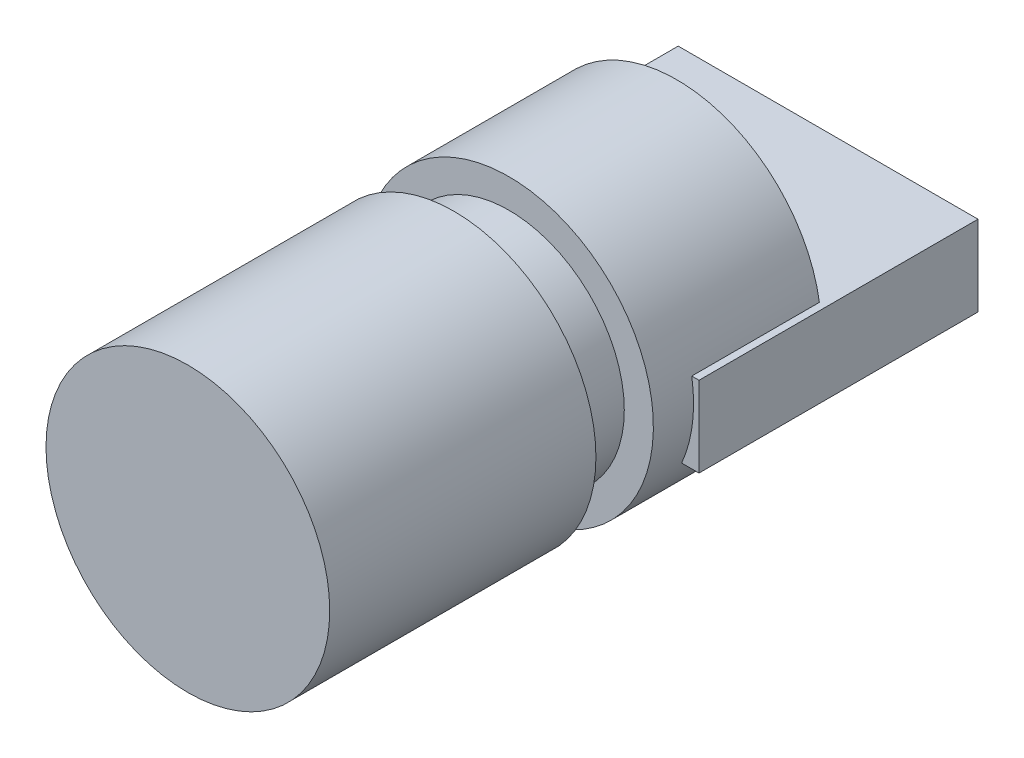
SolidWorks part; units mm, degrees
ref_plane "Front Plane" through (0, 0, 0) normal (0, 0, 1) x (1, 0, 0)
ref_plane "Top Plane" through (0, 0, 0) normal (0, 1, 0) x (1, 0, 0)
ref_plane "Right Plane" through (0, 0, 0) normal (1, 0, 0) x (0, 0, -1)
sketch "Sketch3" plane through (0, 0, 0) normal (0, 0, 1) x (1, 0, 0)
  circle A0 centre (-7.6717, 4.7989) radius 3
  dimension "D1" = 6
extrude "Boss-Extrude1" add sketch "Sketch3" along normal blind 5.63
sketch "Sketch8" plane through (0, 0, 0) normal (0, 0, -1) x (-1, 0, 0)
  circle A0 centre (7.6717, 4.7989) radius 2.44
  circle A1 centre (7.6717, 4.7989) radius 3 construction
  point P2 (0, 0)
  dimension "D1" = 4.88
extrude "Boss-Extrude2" add sketch "Sketch8" along normal blind 1.16
sketch "Sketch9" plane through (0, 0, -1.16) normal (0, 0, -1) x (-1, 0, 0)
  circle A0 centre (7.6717, 4.7989) radius 3.055
  circle A1 centre (7.6717, 4.7989) radius 2.44 construction
  dimension "D1" = 6.11
extrude "Boss-Extrude3" add sketch "Sketch9" along normal blind 3.55
sketch "Sketch12" plane through (0, 0, 5.63) normal (0, 0, 1) x (1, 0, 0)
  line L0 (-10.6717, 4.7989) -> (-4.6717, 4.7989) construction
  line L1 (-7.6717, 7.7989) -> (-7.6717, 1.7989) construction
  circle A0 centre (-7.6717, 4.7989) radius 3 construction
sketch "Sketch13" plane through (0, 0, -4.71) normal (0, 0, -1) x (-1, 0, 0)
  line L0 (4.6167, 4.7989) -> (10.7267, 4.7989) construction
  line L1 (7.6717, 7.8539) -> (7.6717, 1.7439) construction
  circle A0 centre (7.6717, 4.7989) radius 3.055 construction
ref_plane "Horizontal Plane" through (0, 4.7989, 0) normal (0, 1, 0) x (1, 0, 0)
ref_plane "Face Plane" through (0, 0, 5.63) normal (0, 0, 1) x (1, 0, 0)
ref_plane "Vertical Plane" through (-7.6717, 0, 0) normal (-1, 0, 0) x (0, 0, 1)
sketch "Sketch15" plane through (0, 4.7989, 0) normal (0, 1, 0) x (1, 0, 0)
  line L1 (-10.7267, 1.16) -> (-4.6167, 1.16) construction
  line L2 (-10.8417, 2.01) -> (-4.5017, 2.01)
  line L3 (-10.8417, 2.01) -> (-10.8417, 7.91)
  line L4 (-10.8417, 7.91) -> (-4.5017, 7.91)
  line L6 (-4.5017, 2.01) -> (-4.5017, 7.91)
  line L7 (-10.8417, 2.01) -> (-4.5017, 7.91) construction
  line L8 (-10.8417, 7.91) -> (-4.5017, 2.01) construction
  line L9 (-4.6167, 4.71) -> (-10.7267, 4.71) construction
  point P0 (-7.6717, 4.96)
  point P7 (0, 0)
  point P10 (0, 0)
  point P11 (0, 0)
  point P12 (-7.6717, 4.71)
  dimension "D1" = 5.9
  dimension "D2" = 6.34
  dimension "D3" = 6.75
extrude "Boss-Extrude4" add sketch "Sketch15" against normal blind 1.7 from offset 0.485 contours L2 L6 L4 L3
